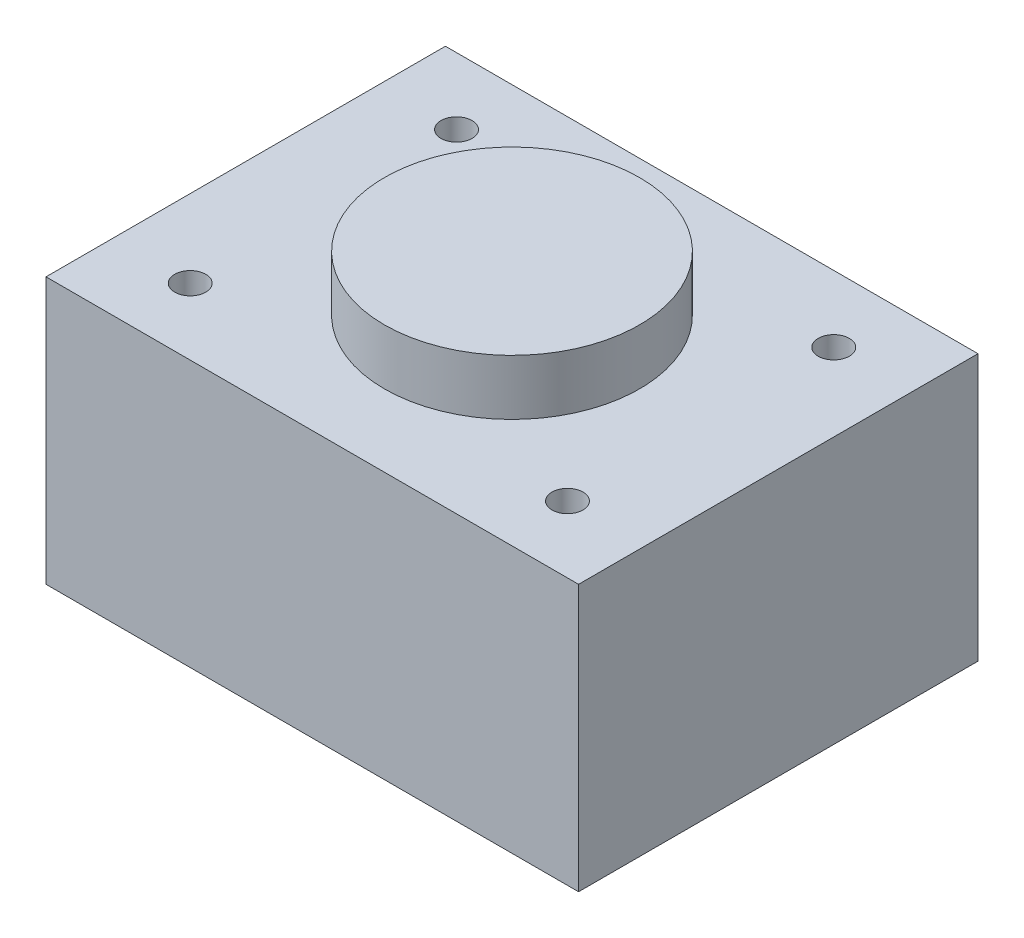
SolidWorks part; units mm, degrees
ref_plane "前视基准面" through (0, 0, 0) normal (0, 0, 1) x (1, 0, 0)
ref_plane "上视基准面" through (0, 0, 0) normal (0, 1, 0) x (1, 0, 0)
ref_plane "右视基准面" through (0, 0, 0) normal (1, 0, 0) x (0, 0, -1)
other "Configuration Table"
sketch "01_Housing_Profile" plane through (0, 0, 0) normal (0, 1, 0) x (1, 0, 0)
  line L1 (-120, -90) -> (120, -90)
  line L2 (-120, -90) -> (-120, 90)
  line L3 (-120, 90) -> (120, 90)
  line L4 (120, -90) -> (120, 90)
  line L5 (-120, -90) -> (120, 90) construction
  line L6 (-120, 90) -> (120, -90) construction
  circle A0 centre (-85, -60) radius 7
  circle A1 centre (85, -60) radius 7
  circle A2 centre (-85, 60) radius 7
  circle A3 centre (85, 60) radius 7
  point P0 (0, 0)
extrude "01_Housing_Block" add sketch "01_Housing_Profile" along normal blind 120
sketch "02_Face_Boss_Profile" plane through (0, 0, 0) normal (0, 1, 0) x (1, 0, 0)
  circle A0 centre (0, 0) radius 57.5
extrude "02_Face_Locating_Boss" add sketch "02_Face_Boss_Profile" along normal blind 145
